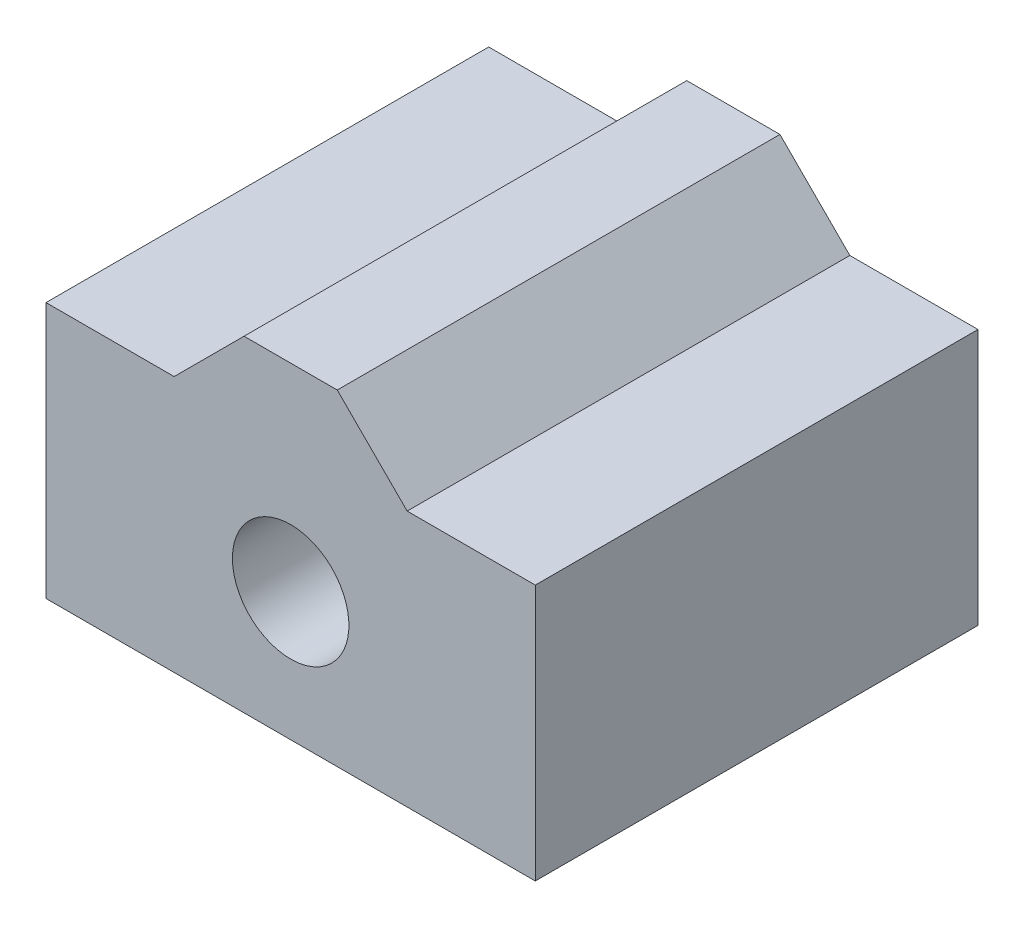
SolidWorks part; units mm, degrees
ref_plane "Front Plane" through (0, 0, 0) normal (0, 0, 1) x (1, 0, 0)
ref_plane "Top Plane" through (0, 0, 0) normal (0, 1, 0) x (1, 0, 0)
ref_plane "Right Plane" through (0, 0, 0) normal (1, 0, 0) x (0, 0, -1)
sketch "Sketch1" plane through (0, 0, 0) normal (0, 0, 1) x (1, 0, 0)
  line L0 (-3.175, 13.4937) -> (-7.9375, 8.7312)
  line L1 (-16.6687, -8.7312) -> (16.6688, -8.7312)
  line L2 (-16.6687, -8.7312) -> (-16.6687, 8.7312)
  line L3 (-16.6687, 8.7312) -> (16.6688, 8.7312)
  line L4 (16.6688, -8.7312) -> (16.6688, 8.7312)
  line L5 (-16.6687, -8.7312) -> (16.6688, 8.7312) construction
  line L6 (-16.6687, 8.7312) -> (16.6688, -8.7312) construction
  line L7 (-3.175, 8.7312) -> (3.175, 8.7312)
  line L8 (-3.175, 8.7312) -> (-3.175, 13.4937)
  line L9 (-3.175, 13.4937) -> (3.175, 13.4937)
  line L10 (3.175, 8.7312) -> (3.175, 13.4937)
  line L11 (3.175, 13.4937) -> (7.9375, 8.7312)
  line L12 (0, 13.4937) -> (0, 8.7312) construction
  circle A0 centre (0, 0) radius 3.9688
  point P0 (0, 0)
  dimension "D7" = 7.9375
  dimension "D1" = 33.3375
  dimension "D2" = 17.4625
  dimension "D3" = 4.7625
  dimension "D4" = 15.875
  dimension "D5" = 45
  dimension "D6" = 6.35
extrude "Boss-Extrude1" add sketch "Sketch1" along normal blind 30.1625 contours L1 L4 L3 L2 | L3 L8 L0 | L3 L10 L9 L8 | L11 L10 L3
